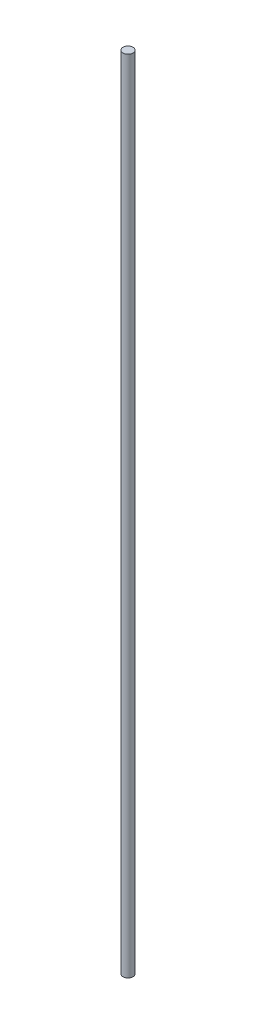
SolidWorks part; units mm, degrees
ref_plane "Front Plane" through (0, 0, 0) normal (0, 0, 1) x (1, 0, 0)
ref_plane "Top Plane" through (0, 0, 0) normal (0, 1, 0) x (1, 0, 0)
ref_plane "Right Plane" through (0, 0, 0) normal (1, 0, 0) x (0, 0, -1)
sketch "Sketch1" plane through (0, 0, 0) normal (0, 1, 0) x (1, 0, 0)
  circle A0 centre (0, 0) radius 4
  dimension "D1" = 8
extrude "Boss-Extrude1" add sketch "Sketch1" along normal blind 635
